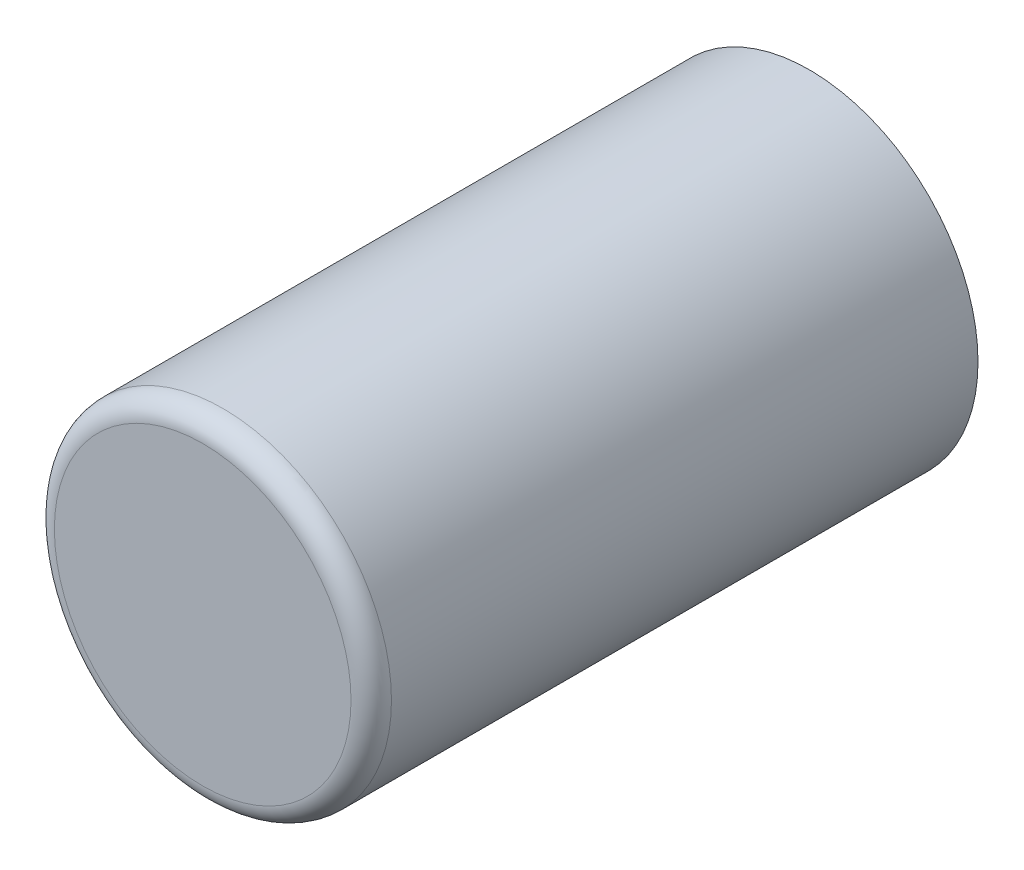
SolidWorks part; units mm, degrees
material "PVC 0.007 Plasticized"
ref_plane "Front Plane" through (0, 0, 0) normal (0, 0, 1) x (1, 0, 0)
ref_plane "Top Plane" through (0, 0, 0) normal (0, 1, 0) x (1, 0, 0)
ref_plane "Right Plane" through (0, 0, 0) normal (1, 0, 0) x (0, 0, -1)
sketch "Sketch1" plane through (0, 0, 0) normal (0, 0, 1) x (1, 0, 0)
  circle A0 centre (0, 0) radius 2.5
  dimension "D1" = 5
extrude "Boss-Extrude1" add sketch "Sketch1" along normal blind 9
fillet "Fillet1" radius 0.3 1 edges at (2.5, 0, 9)
sketch "Sketch2" plane through (0, 0, 0) normal (0, 0, -1) x (-1, 0, 0)
  line L1 (-1.5, -1.5) -> (1.5, -1.5)
  line L2 (-1.5, -1.5) -> (-1.5, 1.5)
  line L3 (-1.5, 1.5) -> (1.5, 1.5)
  line L4 (1.5, -1.5) -> (1.5, 1.5)
  line L5 (-1.5, -1.5) -> (1.5, 1.5) construction
  line L6 (-1.5, 1.5) -> (1.5, -1.5) construction
  point P0 (0, 0)
  dimension "D1" = 3
  dimension "D2" = 3
extrude "Cut-Extrude1" cut sketch "Sketch2" against normal blind 4
